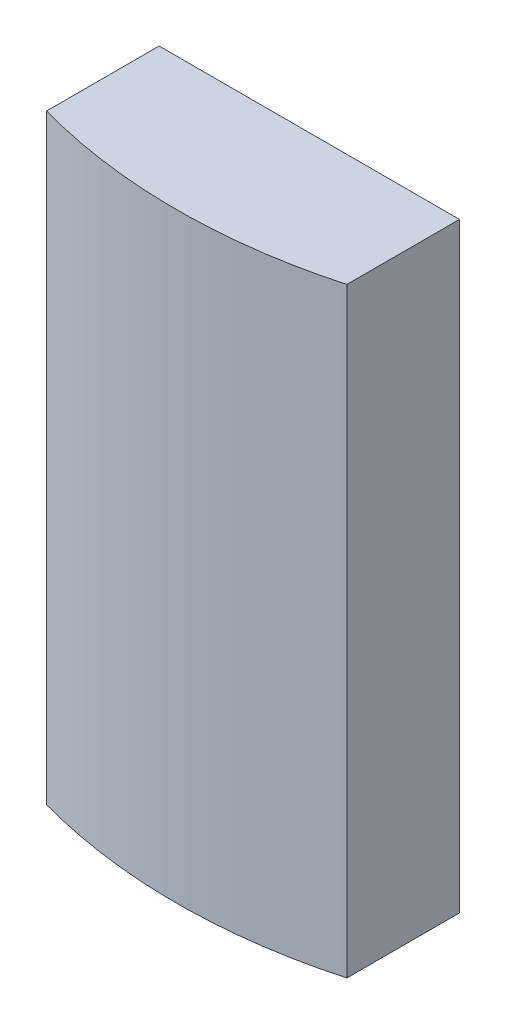
SolidWorks part; units mm, degrees
material "Balsa"
ref_plane "Front Plane" through (0, 0, 0) normal (0, 0, 1) x (1, 0, 0)
ref_plane "Top Plane" through (0, 0, 0) normal (0, 1, 0) x (1, 0, 0)
ref_plane "Right Plane" through (0, 0, 0) normal (1, 0, 0) x (0, 0, -1)
sketch "Sketch1" plane through (0, 0, 0) normal (0, 1, 0) x (1, 0, 0)
  line L0 (0, 0) -> (40, 0)
  line L1 (40, 0) -> (40, -15)
  line L2 (0, 0) -> (0, -15)
  arc A0 (0, -15) -> (40, -15) centre (20, 57.2842) ccw
  dimension "D4" = 75
  dimension "D1" = 15
  dimension "D2" = 15
  dimension "D3" = 40
extrude "Boss-Extrude1" add sketch "Sketch1" along normal blind 80
